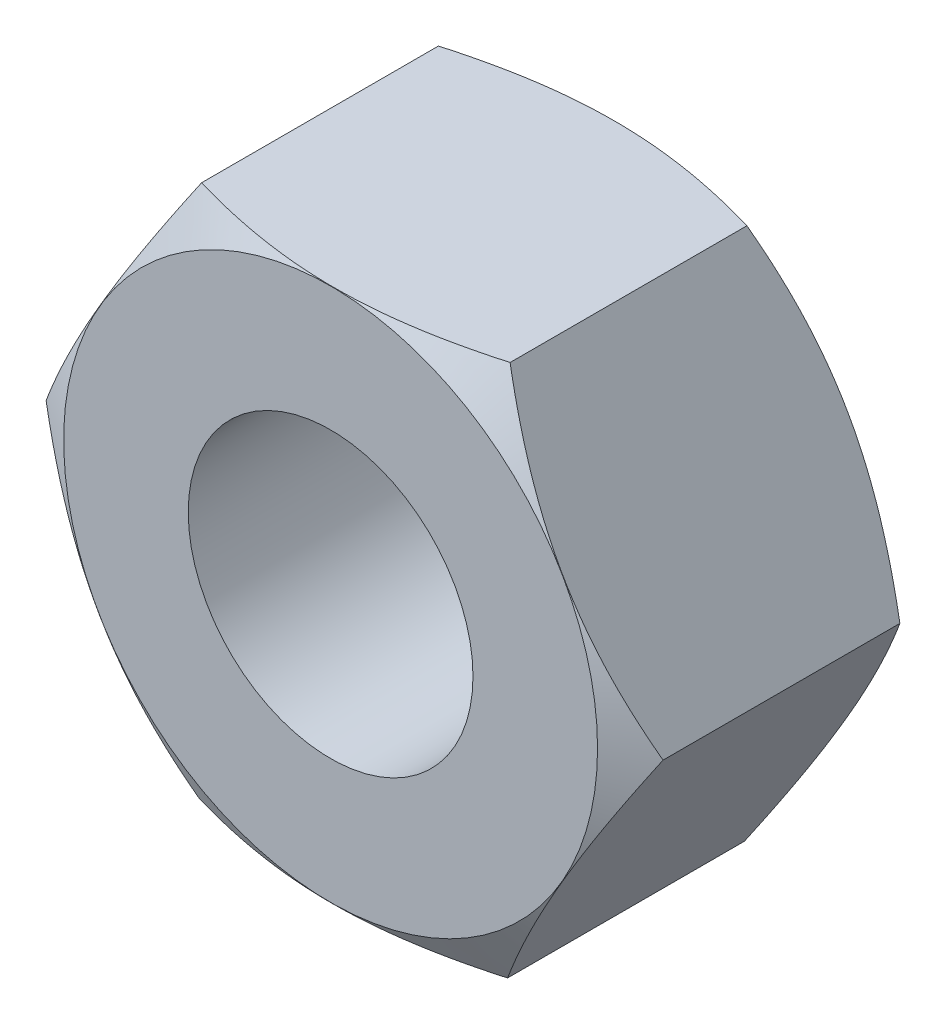
SolidWorks part; units mm, degrees
ref_plane "Front Plane" through (0, 0, 0) normal (0, 0, 1) x (1, 0, 0)
ref_plane "Top Plane" through (0, 0, 0) normal (0, 1, 0) x (1, 0, 0)
ref_plane "Right Plane" through (0, 0, 0) normal (1, 0, 0) x (0, 0, -1)
sketch "Sketch1" plane through (0, 0, 0) normal (0, 0, 1) x (1, 0, 0)
  line L1 (6.5528, 11.2279) -> (-6.4472, 11.2888)
  line L2 (-6.4472, 11.2888) -> (-13, 0.0609)
  line L3 (-13, 0.0609) -> (-6.5528, -11.2279)
  line L4 (-6.5528, -11.2279) -> (6.4472, -11.2888)
  line L5 (6.4472, -11.2888) -> (13, -0.0609)
  line L6 (13, -0.0609) -> (6.5528, 11.2279)
  circle A0 centre (0, 0) radius 11.2585 construction
  circle A1 centre (0, 0) radius 6
  dimension "D2" = 12
  dimension "D1" = 26
extrude "Boss-Extrude1" add sketch "Sketch1" along normal blind 12
sketch "Sketch2" plane through (0, 0, 0) normal (0, 0, -1) x (-1, 0, 0)
  circle A0 centre (0, 0) radius 11.2519
  dimension "D1" = 22.5038
extrude "Cut-Extrude1" cut sketch "Sketch2" against normal through all draft 60 flip side to cut
sketch "Sketch3" plane through (0, 0, 12) normal (0, 0, 1) x (1, 0, 0)
  circle A0 centre (0, 0) radius 11.25
  dimension "D1" = 22.5
extrude "Cut-Extrude3" cut sketch "Sketch3" against normal through all draft 60 flip side to cut
